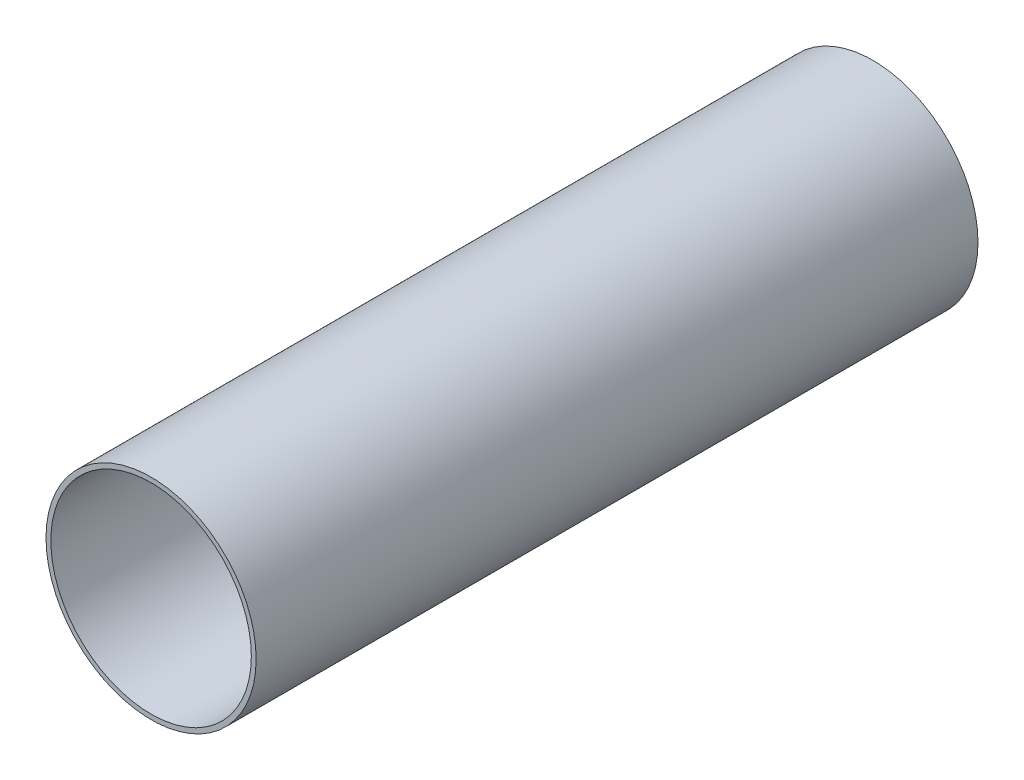
SolidWorks part; units mm, degrees
material "Thornel Mat VMA"
ref_plane "Front Plane" through (0, 0, 0) normal (0, 0, 1) x (1, 0, 0)
ref_plane "Top Plane" through (0, 0, 0) normal (0, 1, 0) x (1, 0, 0)
ref_plane "Right Plane" through (0, 0, 0) normal (1, 0, 0) x (0, 0, -1)
sketch "Sketch1" plane through (0, 0, 0) normal (0, 0, 1) x (1, 0, 0)
  circle A0 centre (0, 0) radius 31.75
  circle A1 centre (0, 0) radius 33.274
  dimension "D1" = 63.5
  dimension "D2" = 66.548
extrude "Boss-Extrude1" add sketch "Sketch1" along normal blind 228.6
